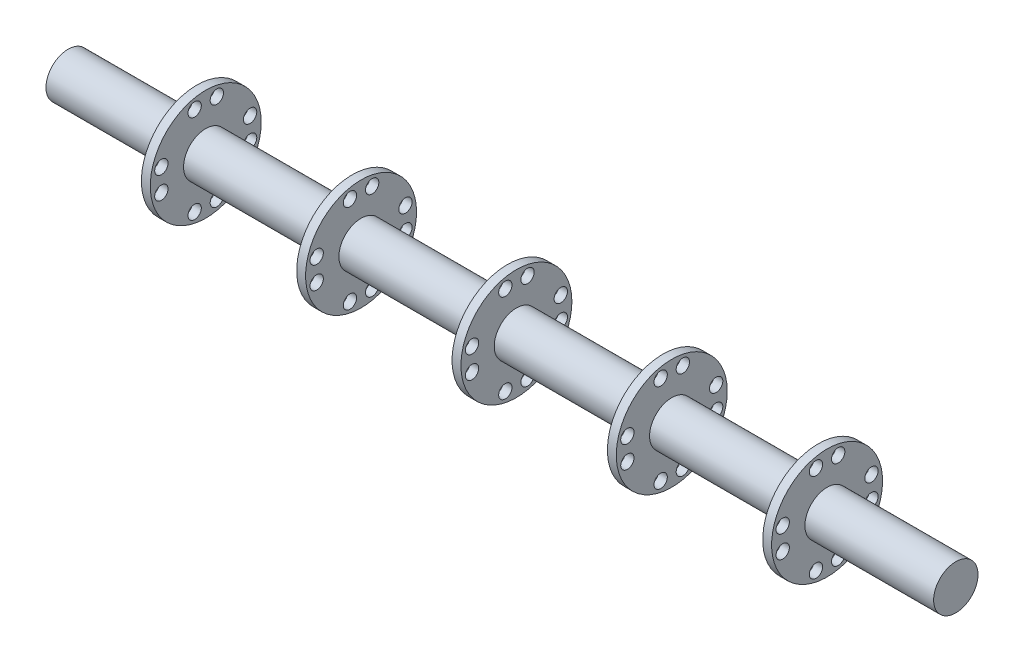
SolidWorks part; units mm, degrees
ref_plane "前视基准面" through (0, 0, 0) normal (0, 0, 1) x (1, 0, 0)
ref_plane "上视基准面" through (0, 0, 0) normal (0, 1, 0) x (1, 0, 0)
ref_plane "右视基准面" through (0, 0, 0) normal (1, 0, 0) x (0, 0, -1)
other "Configuration Table"
sketch "草图1" plane through (0, 0, 0) normal (1, 0, 0) x (0, 0, -1)
  circle A0 centre (0, 0) radius 5
  dimension "D1" = 10
extrude "凸台-拉伸1" add sketch "草图1" along normal mid plane 200
sketch "草图2" plane through (0, 0, 0) normal (1, 0, 0) x (0, 0, -1)
  circle A0 centre (0, 0) radius 12.5
  dimension "D1" = 25
extrude "凸台-拉伸2" add sketch "草图2" along normal mid plane 2
pattern_linear "阵列(线性)1" count 3 spacing 35 along (-1, 0, 0) of "凸台-拉伸2"
pattern_linear "阵列(线性)2" count 3 spacing 35 along (1, 0, 0) of "凸台-拉伸2"
sketch "草图3" plane through (1, 0, 0) normal (1, 0, 0) x (0, 0, -1)
  line L0 (0, 10) -> (2.5, 10)
  line L1 (0, 10) -> (0, 8.5897)
  circle A0 centre (0, 0) radius 10 construction
  circle A2 centre (2.5, 10) radius 1.5
  circle A3 centre (-2.5, 10) radius 1.5
  dimension "D1" = 20
  dimension "D2" = 3
  dimension "D3" = 2.5
extrude "切除-拉伸1" cut sketch "草图3" against normal mid plane 999
pattern_circular "阵列(圆周)1" count 4 over 360 about axis through (0, 0, 0) along (1, 0, 0) of "切除-拉伸1"
